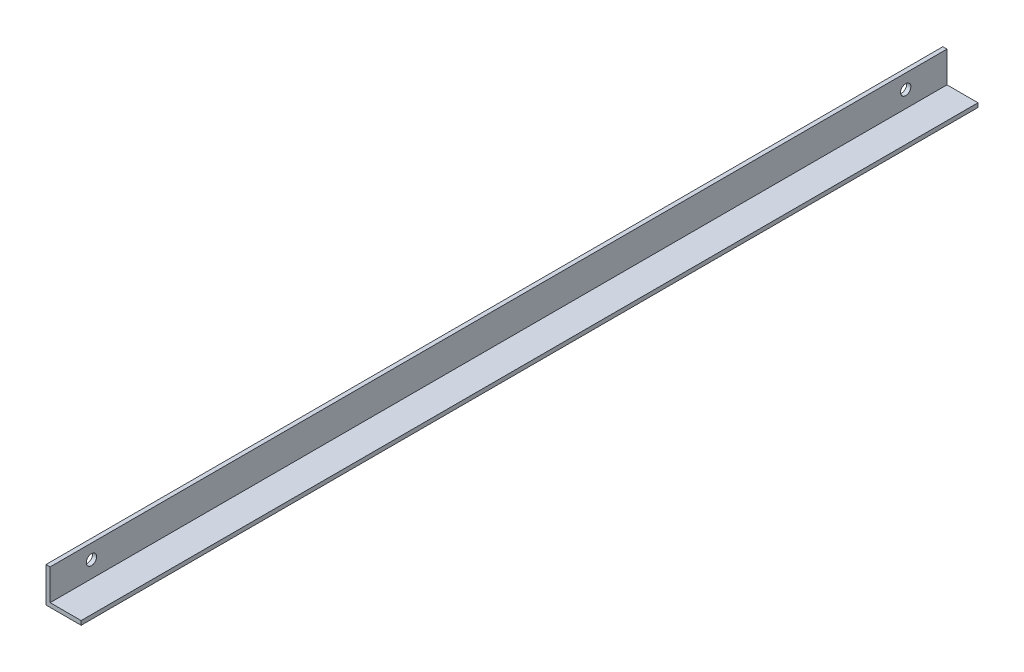
SolidWorks part; units mm, degrees
ref_plane "Спереди" through (0, 0, 0) normal (0, 0, 1) x (1, 0, 0)
ref_plane "Сверху" through (0, 0, 0) normal (0, 1, 0) x (1, 0, 0)
ref_plane "Справа" through (0, 0, 0) normal (1, 0, 0) x (0, 0, -1)
sketch "Эскиз1" plane through (0, 0, 0) normal (0, 0, 1) x (1, 0, 0)
  line L0 (0, 0) -> (0, 13)
  line L1 (0, 13) -> (-2, 13)
  line L2 (-2, 13) -> (-2, -2)
  line L3 (-2, -2) -> (13, -2)
  line L4 (13, -2) -> (13, 0)
  line L5 (13, 0) -> (0, 0)
  dimension "D1" = 2
  dimension "D2" = 2
  dimension "D3" = 15
  dimension "D4" = 15
extrude "Бобышка-Вытянуть1" add sketch "Эскиз1" against normal blind 434
sketch "Эскиз2" plane through (-2, 0, 0) normal (-1, 0, 0) x (0, 0, 1)
  line L0 (0, -2) -> (0, 8)
  line L2 (0, 13) -> (0, -2) construction
  line L3 (0, 8) -> (-20, 8)
  line L4 (-217, 13) -> (-217, -2)
  line L5 (-434, 13) -> (0, 13) construction
  line L6 (-434, -2) -> (0, -2) construction
  line L7 (-434, 8) -> (-414, 8)
  line L8 (-434, -2) -> (-434, 8)
  circle A0 centre (-20, 8) radius 2.5
  circle A1 centre (-414, 8) radius 2.5
  dimension "D3" = 5
  dimension "D1" = 10
  dimension "D2" = 20
extrude "Вырез-Вытянуть1" cut sketch "Эскиз2" against normal through all
sketch "Эскиз3" plane through (0, 0, -434) normal (0, 0, -1) x (-1, 0, 0)
  line L1 (0, 13) -> (2, 13)
  line L2 (0, 13) -> (0, 15)
  line L3 (0, 15) -> (2, 15)
  line L4 (2, 13) -> (2, 15)
  line L5 (-13, -2) -> (-15, -2)
  line L6 (-13, -2) -> (-13, 0)
  line L7 (-13, 0) -> (-15, 0)
  line L8 (-15, -2) -> (-15, 0)
  dimension "D1" = 2
  dimension "D2" = 2
extrude "Бобышка-Вытянуть2" add sketch "Эскиз3" against normal up to surface (434 mm away) up to face at (3.6667, 3.6667, 0)
